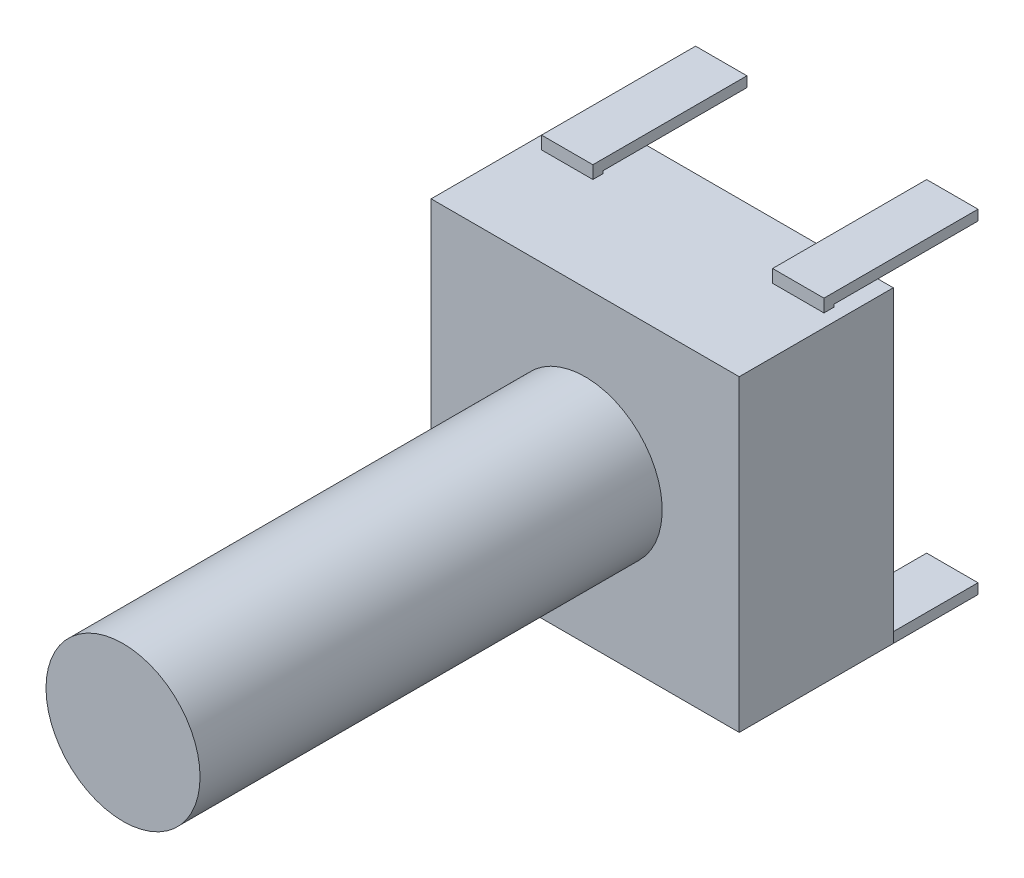
SolidWorks part; units mm, degrees
ref_plane "前视基准面" through (0, 0, 0) normal (0, 0, 1) x (1, 0, 0)
ref_plane "上视基准面" through (0, 0, 0) normal (0, 1, 0) x (1, 0, 0)
ref_plane "右视基准面" through (0, 0, 0) normal (1, 0, 0) x (0, 0, -1)
sketch "草图1" plane through (0, 0, 0) normal (0, 0, 1) x (1, 0, 0)
  line L0 (-1000, 0) -> (49000, 0) construction
  line L1 (0, -1000) -> (0, 49000) construction
  line L2 (-3, 3) -> (3, 3)
  line L3 (3, 3) -> (3, -3)
  line L4 (-3, 3) -> (-3, -3)
  line L5 (-3, -3) -> (3, -3)
  point P10 (0, 3)
  point P11 (3, 0)
  point P12 (-3, 0)
  dimension "D1" = 6
  dimension "D2" = 6
extrude "凸台-拉伸1" add sketch "草图1" along normal blind 3
sketch "草图2" plane through (0, 0, 3) normal (0, 0, 1) x (1, 0, 0)
  circle A0 centre (0, 0) radius 1.5
extrude "凸台-拉伸2" add sketch "草图2" along normal blind 9
sketch "草图4" plane through (0, -3, 0) normal (0, -1, 0) x (1, 0, 0)
  line L0 (0, -1000) -> (0, 49000) construction
  line L1 (2.25, 2.1495) -> (2.25, -0.7714) construction
  line L2 (-2.25, 2.1495) -> (-2.25, -0.7714) construction
  line L3 (-3.6318, 1) -> (3.4524, 1) construction
  line L4 (-3, 0) -> (3, 0) construction
  line L5 (1.75, 1.1) -> (2.75, 1.1)
  line L6 (2.75, 1.1) -> (2.75, 0.9)
  line L7 (1.75, 1.1) -> (1.75, 0.9)
  line L8 (1.75, 0.9) -> (2.75, 0.9)
  point P16 (2.25, 1.1)
  point P17 (2.75, 1)
  point P18 (1.75, 1)
  dimension "D1" = 4.5
  dimension "D2" = 1
  dimension "D3" = 0.2
  dimension "D4" = 1
ref_plane "基准面1" through (2.25, 0, 0) normal (1, 0, 0) x (0, 0, -1)
sketch "草图6" plane through (2.25, 0, 0) normal (1, 0, 0) x (0, 0, -1)
  line L0 (-1000, 0) -> (49000, 0) construction
  line L1 (-4.4082, -3.25) -> (1.7946, -3.25) construction
  line L2 (-4.4082, 3.25) -> (1.7946, 3.25) construction
  line L3 (-1.1, -3) -> (-1.1, -3.25)
  line L4 (-1.1, -3.25) -> (1.9, -3.25)
  dimension "D1" = 6.5
  dimension "D2" = 3
sweep "扫描3" add profiles "草图4" path "草图6"
mirror "镜向1" about plane through (0, 0, 0) normal (1, 0, 0) of "扫描3"
mirror "镜向2" about plane through (0, 0, 0) normal (0, 1, 0) of "镜向1", "扫描3"
